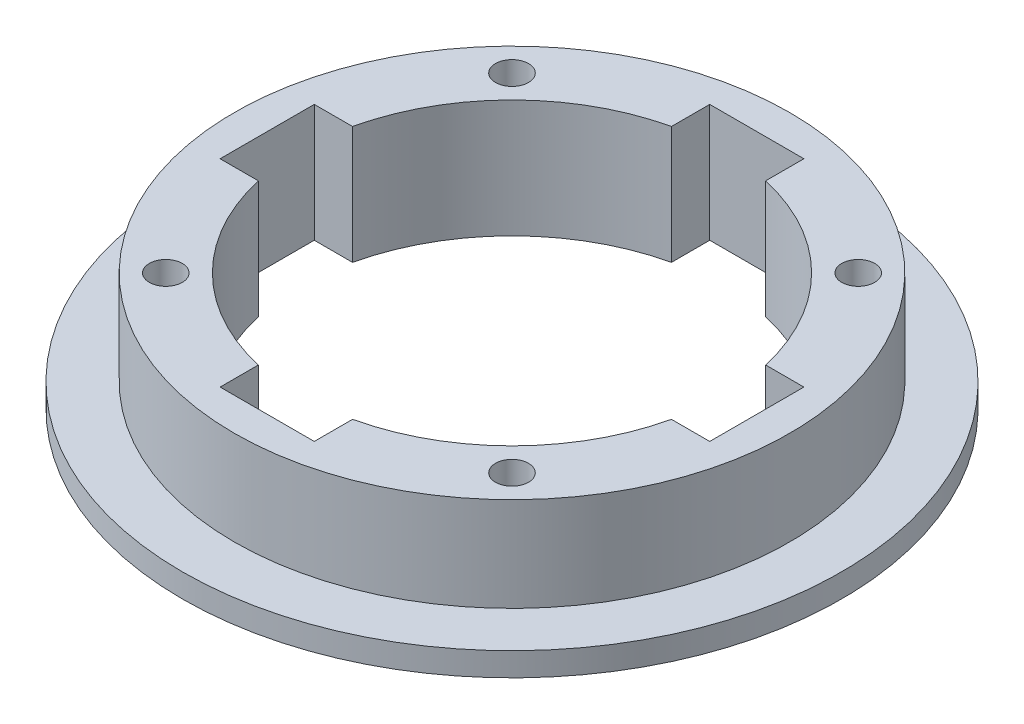
SolidWorks part; units mm, degrees
ref_plane "Front Plane" through (0, 0, 0) normal (0, 0, 1) x (1, 0, 0)
ref_plane "Top Plane" through (0, 0, 0) normal (0, 1, 0) x (1, 0, 0)
ref_plane "Right Plane" through (0, 0, 0) normal (1, 0, 0) x (0, 0, -1)
sketch "Sketch1" plane through (0, 0, 0) normal (0, 1, 0) x (1, 0, 0)
  circle A0 centre (0, 0) radius 35
  circle A1 centre (0, 0) radius 30 construction
  circle A2 centre (0, 0) radius 22.5
  dimension "D1" = 70
  dimension "D2" = 60
  dimension "D3" = 45
extrude "Boss-Extrude1" add sketch "Sketch1" along normal blind 2.5
sketch "Sketch2" plane through (0, 2.5, 0) normal (0, 1, 0) x (1, 0, 0)
  circle A0 centre (0, 0) radius 29.5
  circle A1 centre (0, 0) radius 22.5
  dimension "D1" = 59
  dimension "D2" = 45
extrude "Boss-Extrude2" add sketch "Sketch2" along normal blind 10
sketch "Sketch3" plane through (0, 12.5, 0) normal (0, 1, 0) x (1, 0, 0)
  line L0 (0, 0) -> (-35, 0) construction
  line L1 (0, 0) -> (0, -35) construction
  line L2 (-5, 21.9374) -> (-5, 26)
  line L3 (5, -26) -> (-5, -26)
  line L4 (5, -26) -> (5, -21.9374)
  line L5 (5, 26) -> (-5, 26)
  line L6 (-5, -26) -> (-5, -21.9374)
  line L7 (5, -26) -> (-5, 26) construction
  line L8 (5, 26) -> (-5, -26) construction
  line L9 (26, -5) -> (21.9374, -5)
  line L10 (26, -5) -> (26, 5)
  line L11 (26, 5) -> (21.9374, 5)
  line L12 (-26, -5) -> (-26, 5)
  line L13 (26, -5) -> (-26, 5) construction
  line L14 (26, 5) -> (-26, -5) construction
  line L16 (-21.9374, -5) -> (-26, -5)
  line L17 (-21.9374, 5) -> (-26, 5)
  line L18 (5, 21.9374) -> (5, 26)
  circle A0 centre (0, 0) radius 35 construction
  arc A1 (21.9374, 5) -> (5, 21.9374) centre (0, 0) ccw
  arc A2 (-5, 21.9374) -> (-21.9374, 5) centre (0, 0) ccw
  arc A3 (-21.9374, -5) -> (-5, -21.9374) centre (0, 0) ccw
  arc A4 (5, -21.9374) -> (21.9374, -5) centre (0, 0) ccw
  dimension "D1" = 45
  dimension "D2" = 52
  dimension "D3" = 10
  dimension "D4" = 52
  dimension "D5" = 10
extrude "Cut-Extrude1" cut sketch "Sketch3" against normal through all
sketch "Sketch4" plane through (0, 12.5, 0) normal (0, 1, 0) x (1, 0, 0)
  line L0 (0, 0) -> (-45.5771, 0) construction
  line L1 (0, 0) -> (-35.3553, -35.3553) construction
  circle A0 centre (0, 0) radius 26 construction
  circle A1 centre (-18.3848, -18.3848) radius 1.75
  circle A2 centre (-18.3848, 18.3848) radius 1.75
  circle A3 centre (18.3848, 18.3848) radius 1.75
  circle A4 centre (18.3848, -18.3848) radius 1.75
  point P16 (0, 0)
  dimension "D1" = 52
  dimension "D2" = 45
  dimension "D3" = 3.5
  dimension "D4" = 4
extrude "Cut-Extrude2" cut sketch "Sketch4" against normal through all
